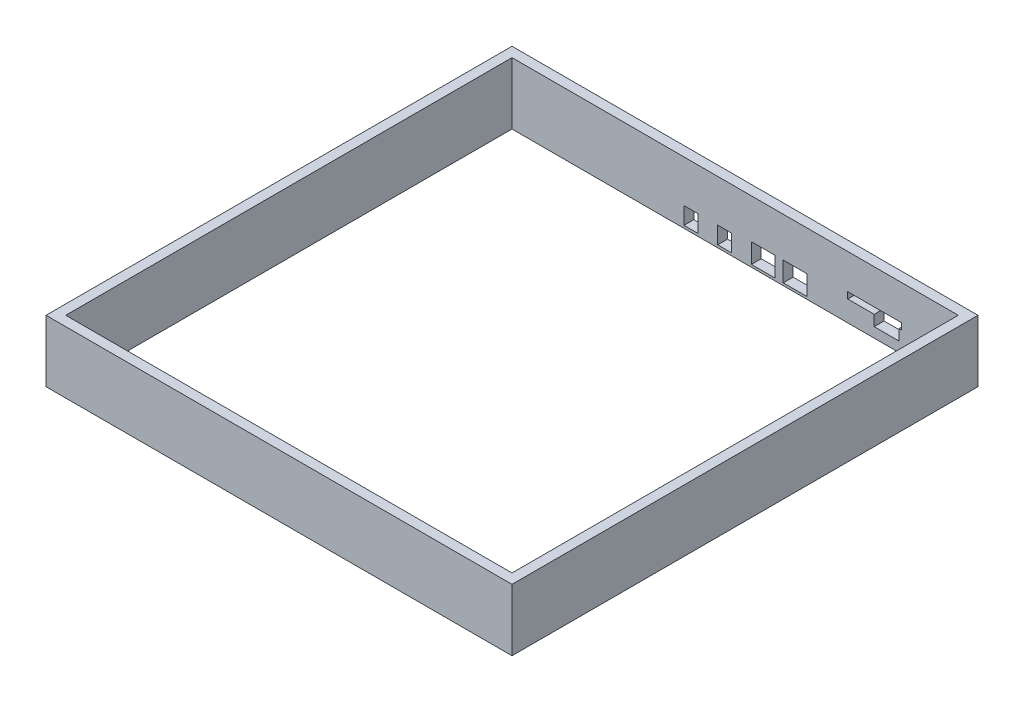
SolidWorks part; units mm, degrees
ref_plane "Front Plane" through (0, 0, 0) normal (0, 0, 1) x (1, 0, 0)
ref_plane "Top Plane" through (0, 0, 0) normal (0, 1, 0) x (1, 0, 0)
ref_plane "Right Plane" through (0, 0, 0) normal (1, 0, 0) x (0, 0, -1)
sketch "Sketch1" plane through (0, 0, 0) normal (0, 1, 0) x (1, 0, 0)
  line L1 (-150, -150) -> (150, -150)
  line L2 (-150, -150) -> (-150, 150)
  line L3 (-150, 150) -> (150, 150)
  line L4 (150, -150) -> (150, 150)
  line L5 (-150, -150) -> (150, 150) construction
  line L6 (-150, 150) -> (150, -150) construction
  line L7 (-143.65, -143.65) -> (143.65, -143.65)
  line L8 (-143.65, -143.65) -> (-143.65, 143.65)
  line L9 (-143.65, 143.65) -> (143.65, 143.65)
  line L10 (143.65, -143.65) -> (143.65, 143.65)
  line L11 (-143.65, -143.65) -> (143.65, 143.65) construction
  line L12 (-143.65, 143.65) -> (143.65, -143.65) construction
  point P0 (0, 0)
  point P6 (0, 0)
  dimension "D1" = 300
  dimension "D2" = 300
  dimension "D3" = 6.35
extrude "Boss-Extrude1" add sketch "Sketch1" along normal blind 39.8272
sketch "Sketch3" plane through (0, 0, -150) normal (0, 0, -1) x (-1, 0, 0)
  line L0 (-105.5176, 19.7358) -> (-89.5156, 19.7358) construction
  line L1 (-72.4976, 17.4188) -> (-107.152, 17.4188)
  line L2 (-72.4976, 17.4188) -> (-72.4976, 13.306)
  line L3 (-72.4976, 13.306) -> (-107.152, 13.306)
  line L4 (-107.152, 17.4188) -> (-107.152, 13.306)
  line L5 (-89.5156, 6.4008) -> (-105.5176, 6.4008)
  line L6 (-89.5156, 6.4008) -> (-89.5156, 19.7358)
  line L7 (-89.5156, 19.7358) -> (-105.5176, 19.7358)
  line L8 (-105.5176, 6.4008) -> (-105.5176, 19.7358)
  line L9 (-105.5176, 19.7358) -> (-105.5176, 6.4008) construction
  line L11 (-46.2684, 14.2748) -> (-30.9684, 14.2748)
  line L12 (-46.2684, 14.2748) -> (-46.2684, 1.5748)
  line L13 (-46.2684, 1.5748) -> (-30.9684, 1.5748)
  line L14 (-30.9684, 14.2748) -> (-30.9684, 1.5748)
  line L15 (-25.7426, 14.2748) -> (-10.4426, 14.2748)
  line L16 (-25.7426, 14.2748) -> (-25.7426, 1.5748)
  line L17 (-25.7426, 1.5748) -> (-10.4426, 1.5748)
  line L18 (-10.4426, 14.2748) -> (-10.4426, 1.5748)
  line L23 (11.2574, 1.6748) -> (11.2574, 12.6748) construction
  line L24 (2.2574, 1.6748) -> (11.2574, 1.6748)
  line L25 (2.2574, 1.6748) -> (2.2574, 12.6748)
  line L30 (2.2574, 12.6748) -> (11.2574, 12.6748)
  line L31 (26.9415, 10.936) -> (28.4574, 8.1748) construction
  line L32 (11.2574, 1.6748) -> (11.2574, 12.6748)
  line L34 (23.9574, 12.6748) -> (32.9574, 12.6748)
  line L35 (23.9574, 12.6748) -> (23.9574, 1.6748)
  line L36 (23.9574, 1.6748) -> (32.9574, 1.6748)
  line L37 (32.9574, 12.6748) -> (32.9574, 1.6748)
  circle A3 centre (28.4574, 8.1748) radius 3.15 construction
  arc A4 (26.9415, 10.936) -> (26.9415, 5.4136) centre (28.4574, 8.1748) ccw
extrude "Cut-Extrude1" cut sketch "Sketch3" against normal up to next
